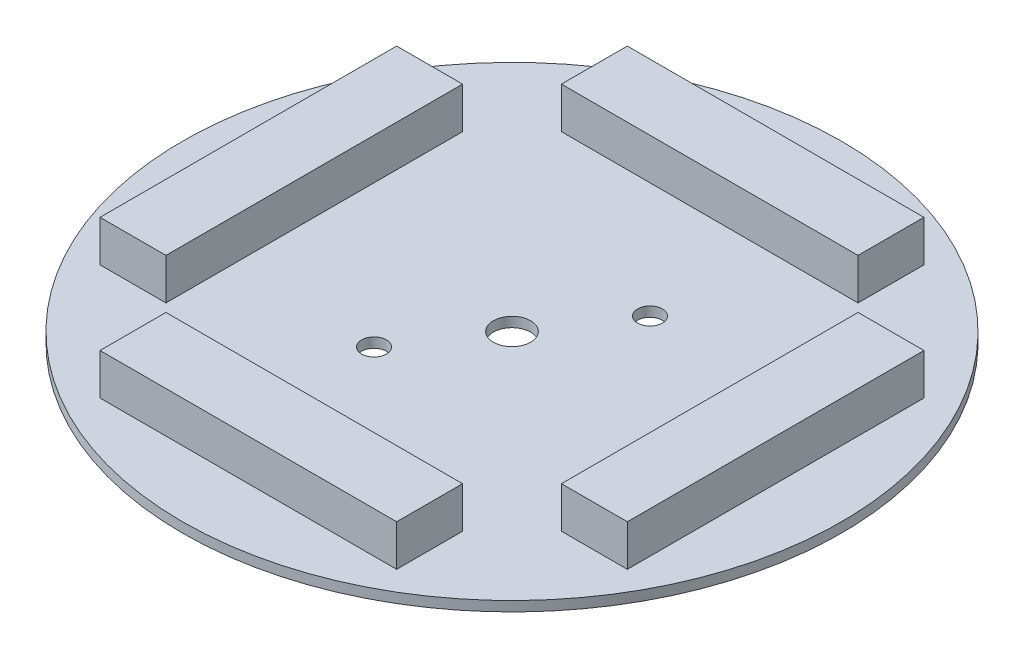
SolidWorks part; units mm, degrees
material "A-Glass Fiber"
ref_plane "Front Plane" through (0, 0, 0) normal (0, 0, 1) x (1, 0, 0)
ref_plane "Top Plane" through (0, 0, 0) normal (0, 1, 0) x (1, 0, 0)
ref_plane "Right Plane" through (0, 0, 0) normal (1, 0, 0) x (0, 0, -1)
sketch "Sketch1" plane through (0, 0, 0) normal (0, 1, 0) x (1, 0, 0)
  line L0 (-11.1839, -16.5808) -> (11.1839, 16.5808) construction
  line L1 (0, 20) -> (0, -20) construction
  circle A0 centre (0, 0) radius 20
  circle A1 centre (0, 0) radius 1.1303
  circle A2 centre (3.3725, 5) radius 0.75
  circle A3 centre (-3.3725, -5) radius 0.75
  dimension "D1" = 40
  dimension "D5" = 2.2606
  dimension "D6" = 1.5
  dimension "D7" = 1.5
  dimension "D2" = 34
  dimension "D3" = 5
  dimension "D4" = 5
extrude "PCB" add sketch "Sketch1" along normal blind 0.6 contours A0 | A3 | A1 | A2
sketch "Sketch2" plane through (0, 0.6, 0) normal (0, 1, 0) x (1, 0, 0)
  line L0 (0, 20) -> (0, 0) construction
  line L1 (-9, 16) -> (9, 16)
  line L2 (-9, 16) -> (-9, 12)
  line L3 (-9, 12) -> (9, 12)
  line L4 (9, 16) -> (9, 12)
  circle A0 centre (0, 0) radius 20 construction
  point P9 (0, 16)
  dimension "D1" = 4
  dimension "D2" = 18
  dimension "D3" = 16
extrude "Hirose Connector Stack" add sketch "Sketch2" along normal blind 2.5 contours L1 L4 L3 L2
pattern_circular "CirPattern1" count 4 over 360 about axis through (0, 0, 0) along (0, 1, 0) of "Hirose Connector Stack"
